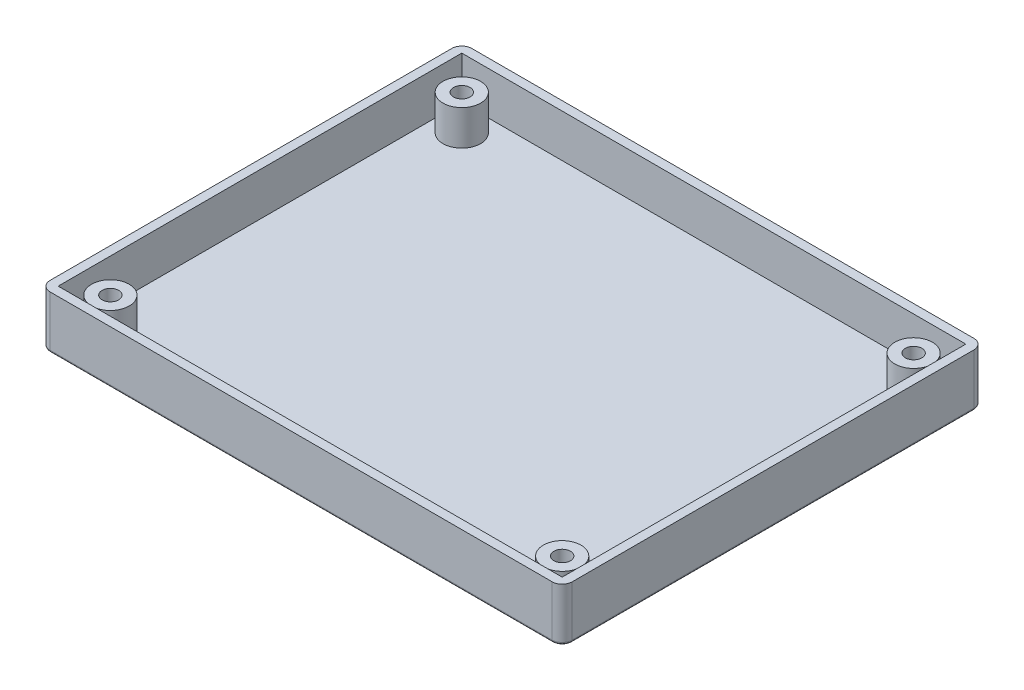
SolidWorks part; units mm, degrees
ref_plane "Plan de face" through (0, 0, 0) normal (0, 0, 1) x (1, 0, 0)
ref_plane "Plan de dessus" through (0, 0, 0) normal (0, 1, 0) x (1, 0, 0)
ref_plane "Plan de droite" through (0, 0, 0) normal (1, 0, 0) x (0, 0, -1)
sketch "Esquisse1" plane through (0, 0, 0) normal (0, 1, 0) x (1, 0, 0)
  line L0 (-52, -42) -> (-52, 42)
  line L1 (-50, -40) -> (50, -40)
  line L2 (-50, -40) -> (-50, 40) construction
  line L3 (-50, 40) -> (50, 40)
  line L4 (50, -40) -> (50, 40)
  line L5 (-50, -40) -> (50, 40) construction
  line L6 (-50, 40) -> (50, -40) construction
  line L7 (-52, 42) -> (52, 42)
  line L8 (52, -42) -> (52, 42)
  line L9 (-52, -42) -> (52, -42)
  point P0 (0, 0)
  dimension "D1" = 100
  dimension "D2" = 80
  dimension "D3" = 2
extrude "Boss.-Extru.1" add sketch "Esquisse1" along normal blind 2
sketch "Esquisse2" plane through (0, 2, 0) normal (0, 1, 0) x (1, 0, 0)
  line L1 (-45, -35) -> (45, -35) construction
  line L2 (-45, -35) -> (-45, 35) construction
  line L3 (-45, 35) -> (45, 35) construction
  line L4 (45, -35) -> (45, 35) construction
  line L5 (-45, -35) -> (45, 35) construction
  line L6 (-45, 35) -> (45, -35) construction
  circle A0 centre (-45, 35) radius 3.75
  circle A1 centre (45, 35) radius 3.75
  circle A2 centre (45, -35) radius 3.75
  circle A3 centre (-45, -35) radius 3.75
  point P0 (0, 0)
  dimension "D3" = 7.5
  dimension "D1" = 90
  dimension "D2" = 70
extrude "Boss.-Extru.2" add sketch "Esquisse2" along normal blind 7
sketch "Esquisse3" plane through (0, 2, 0) normal (0, 1, 0) x (1, 0, 0)
  line L0 (-52, -42) -> (-52, 42) construction
  line L1 (-52, -42) -> (-52, 42)
  line L2 (-52, 42) -> (52, 42) construction
  line L3 (-52, 42) -> (52, 42)
  line L4 (-50.2, 40.2) -> (-50.2, -40.2)
  line L5 (-50.2, -40.2) -> (50.2, -40.2)
  line L6 (50.2, -40.2) -> (50.2, 40.2)
  line L7 (50.2, 40.2) -> (-50.2, 40.2)
  line L8 (-52, 42) -> (-52, -42)
  line L9 (-52, -42) -> (52, -42)
  line L10 (52, -42) -> (52, 42)
  line L11 (52, 42) -> (-52, 42)
  line L12 (-52, 42) -> (-52, -42)
  line L13 (-52, -42) -> (52, -42)
  line L14 (52, -42) -> (52, 42)
  line L15 (52, 42) -> (-52, 42)
  dimension "D1" = 0
  dimension "D2" = 1.8
extrude "Boss.-Extru.3" add sketch "Esquisse3" along normal blind 8.55 contours L8 L5 L6 L7 L4
sketch "Esquisse4" plane through (0, 9, 0) normal (0, 1, 0) x (1, 0, 0)
  circle A0 centre (-45, 35) radius 1.65
  circle A1 centre (45, 35) radius 1.65
  circle A2 centre (45, -35) radius 1.65
  circle A3 centre (-45, -35) radius 1.65
  dimension "D1" = 3.3
extrude "Enlèv. mat.-Extru.1" cut sketch "Esquisse4" against normal through all
sketch "Esquisse5" plane through (0, 0, 0) normal (0, -1, 0) x (1, 0, 0)
  line L1 (-43.3979, 32.225) -> (-41.7957, 35)
  line L2 (-41.7957, 35) -> (-43.3979, 37.775)
  line L3 (-43.3979, 37.775) -> (-46.6021, 37.775)
  line L4 (-46.6021, 37.775) -> (-48.2043, 35)
  line L5 (-48.2043, 35) -> (-46.6021, 32.225)
  line L6 (-46.6021, 32.225) -> (-43.3979, 32.225)
  line L7 (43.3979, 32.225) -> (46.6021, 32.225)
  line L8 (46.6021, 32.225) -> (48.2043, 35)
  line L9 (48.2043, 35) -> (46.6021, 37.775)
  line L10 (46.6021, 37.775) -> (43.3979, 37.775)
  line L11 (43.3979, 37.775) -> (41.7957, 35)
  line L12 (41.7957, 35) -> (43.3979, 32.225)
  line L13 (43.3979, -32.225) -> (41.7957, -35)
  line L14 (41.7957, -35) -> (43.3979, -37.775)
  line L15 (43.3979, -37.775) -> (46.6021, -37.775)
  line L16 (46.6021, -37.775) -> (48.2043, -35)
  line L17 (48.2043, -35) -> (46.6021, -32.225)
  line L18 (46.6021, -32.225) -> (43.3979, -32.225)
  line L19 (-46.6021, -32.225) -> (-48.2043, -35)
  line L20 (-48.2043, -35) -> (-46.6021, -37.775)
  line L21 (-46.6021, -37.775) -> (-43.3979, -37.775)
  line L22 (-43.3979, -37.775) -> (-41.7957, -35)
  line L23 (-41.7957, -35) -> (-43.3979, -32.225)
  line L24 (-43.3979, -32.225) -> (-46.6021, -32.225)
  circle A0 centre (-45, 35) radius 2.775 construction
  circle A1 centre (45, 35) radius 2.775 construction
  circle A2 centre (45, -35) radius 2.775 construction
  circle A3 centre (-45, -35) radius 2.775 construction
  dimension "D1" = 5.55
extrude "Enlèv. mat.-Extru.2" cut sketch "Esquisse5" against normal blind 3
fillet "Congé1" radius 2 4 edges at (-52, 5.275, -42) (-52, 5.275, 42) (52, 5.275, -42) (52, 5.275, 42)
fillet "Congé2" radius 0.5 8 edges at (-51.4142, 0, -41.4142) (-52, 0, 0) (-51.4142, 0, 41.4142) (0, 0, 42) (51.4142, 0, 41.4142) (52, 0, 0) (51.4142, 0, -41.4142) (0, 0, -42)
